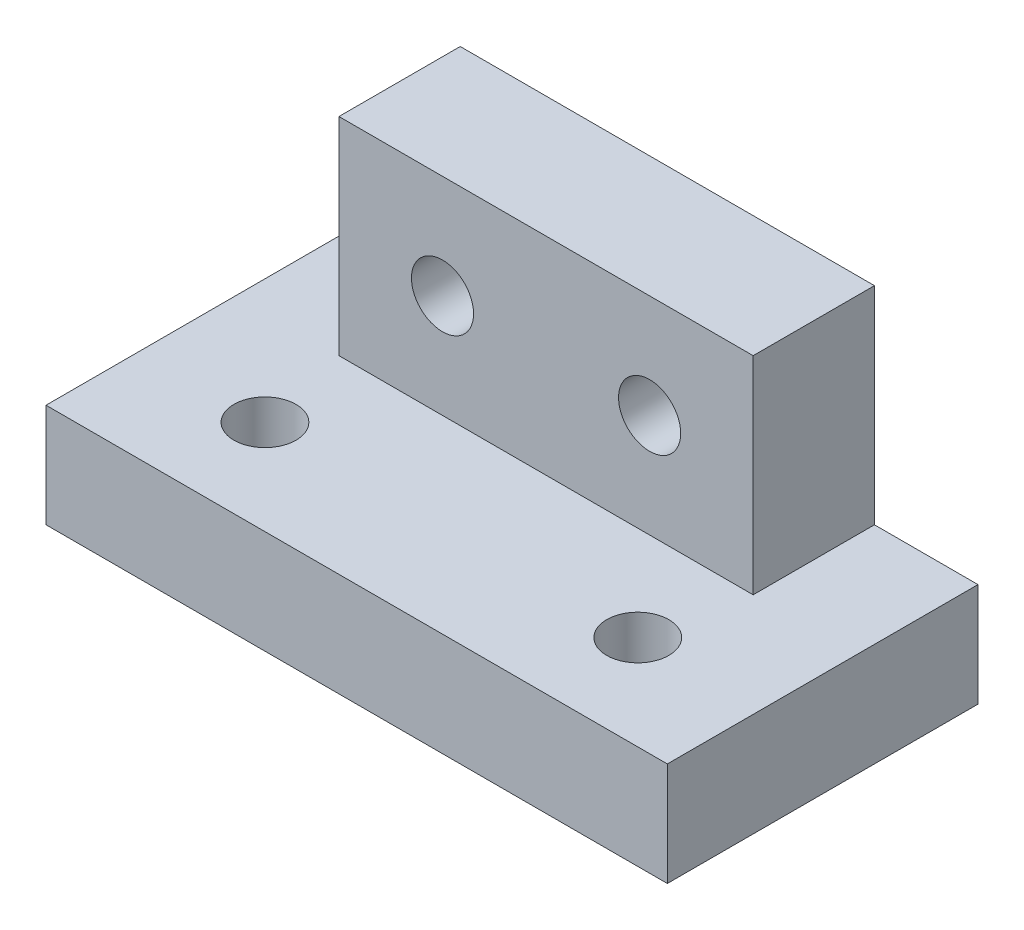
SolidWorks part; units mm, degrees
ref_plane "Спереди" through (0, 0, 0) normal (0, 0, 1) x (1, 0, 0)
ref_plane "Сверху" through (0, 0, 0) normal (0, 1, 0) x (1, 0, 0)
ref_plane "Справа" through (0, 0, 0) normal (1, 0, 0) x (0, 0, -1)
sketch "Эскиз1" plane through (0, 0, 0) normal (0, 1, 0) x (1, 0, 0)
  line L1 (-40.5189, -12.757) -> (-10.5189, -12.757)
  line L2 (-40.5189, -12.757) -> (-40.5189, -27.757)
  line L3 (-40.5189, -27.757) -> (-10.5189, -27.757)
  line L4 (-10.5189, -12.757) -> (-10.5189, -27.757)
extrude "Бобышка-Вытянуть1" add sketch "Эскиз1" along normal blind 5
sketch "Эскиз2" plane through (0, 5, 0) normal (0, 1, 0) x (1, 0, 0)
  line L0 (-25.5189, -12.757) -> (-25.5189, -18.6125) construction
  line L1 (-10.5189, -12.757) -> (-40.5189, -12.757) construction
  line L3 (-35.5189, -12.757) -> (-15.5189, -12.757)
  line L4 (-35.5189, -12.757) -> (-15.5189, -12.757)
  line L5 (-35.5189, -12.757) -> (-35.5189, -18.6125)
  line L6 (-35.5189, -18.6125) -> (-15.5189, -18.6125)
  line L7 (-15.5189, -12.757) -> (-15.5189, -18.6125)
  line M5 (-10.5189, -12.757) -> (-40.5189, -12.757)
  dimension "D2" = 10
  dimension "D3" = 10
extrude "Бобышка-Вытянуть3" add sketch "Эскиз2" along normal blind 10 contours L0 L6 L7 M5 | L0 L4 L5 L6
sketch "Эскиз4" plane through (0, 0, 18.6125) normal (0, 0, 1) x (1, 0, 0)
  line L0 (-25.5189, 35) -> (-25.5189, 5) construction
  line L2 (-40.5189, 5) -> (-10.5189, 5) construction
  line L3 (-25.5189, 10) -> (-15.5189, 10) construction
  line L4 (-20.5189, 10) -> (-20.5189, 5) construction
  line L5 (-35.5189, 5) -> (-15.5189, 5) construction
  line L6 (-25.5189, 10) -> (-33.4793, 10) construction
  line L7 (-30.5189, 10) -> (-30.5189, 5) construction
  circle A0 centre (-20.5189, 10) radius 1.5
  circle A1 centre (-30.5189, 10) radius 1.5
  point P7 (-25.5189, 20)
  dimension "D3" = 5
  dimension "D1" = 5
  dimension "D2" = 5
extrude "Вырез-Вытянуть1" cut sketch "Эскиз4" against normal blind 6
sketch "Эскиз5" plane through (0, 5, 0) normal (0, 1, 0) x (1, 0, 0)
  line L0 (-25.5189, -27.757) -> (-25.5189, -18.6125) construction
  line L1 (-40.5189, -27.757) -> (-10.5189, -27.757) construction
  line L2 (-35.5189, -18.6125) -> (-15.5189, -18.6125) construction
  line L3 (-25.5189, -23.1848) -> (-40.5189, -23.1848) construction
  line L4 (-40.5189, -12.757) -> (-40.5189, -27.757) construction
  line L5 (-25.5189, -23.1848) -> (-10.5189, -23.1848) construction
  line L6 (-10.5189, -27.757) -> (-10.5189, -12.757) construction
  line L7 (-34.5189, -27.757) -> (-34.5189, -18.6125) construction
  line L8 (-35.5189, -18.6125) -> (-15.5189, -18.6125) construction
  line L9 (-16.5189, -27.757) -> (-16.5189, -18.6125) construction
  circle A0 centre (-34.5189, -23.1848) radius 1.5
  circle A1 centre (-16.5189, -23.1848) radius 1.5
  dimension "D3" = 18
  dimension "D1" = 9
  dimension "D2" = 9
extrude "Вырез-Вытянуть2" cut sketch "Эскиз5" against normal blind 5
